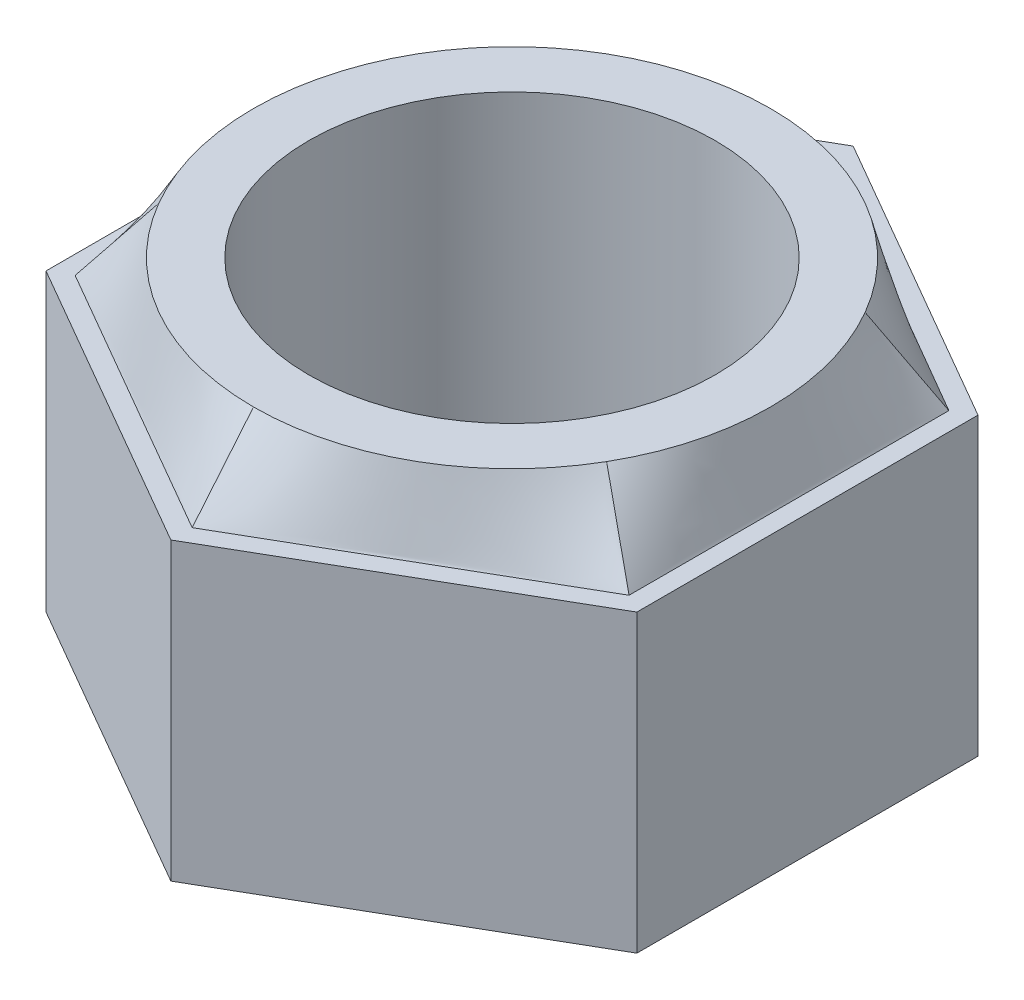
SolidWorks part; units mm, degrees
ref_plane "Front Plane" through (0, 0, 0) normal (0, 0, 1) x (1, 0, 0)
ref_plane "Top Plane" through (0, 0, 0) normal (0, 1, 0) x (1, 0, 0)
ref_plane "Right Plane" through (0, 0, 0) normal (1, 0, 0) x (0, 0, -1)
sketch "Sketch1" plane through (0, 0, 0) normal (0, 1, 0) x (1, 0, 0)
  line L1 (0, 4.6188) -> (-4, 2.3094)
  line L2 (-4, 2.3094) -> (-4, -2.3094)
  line L3 (-4, -2.3094) -> (0, -4.6188)
  line L4 (0, -4.6188) -> (4, -2.3094)
  line L5 (4, -2.3094) -> (4, 2.3094)
  line L6 (4, 2.3094) -> (0, 4.6188)
  circle A0 centre (0, 0) radius 4 construction
  dimension "D1" = 8
extrude "Body" add sketch "Sketch1" along normal blind 4
ref_plane "Plane1" through (0, 5, 0) normal (0, 1, 0) x (1, 0, 0)
sketch "Sketch4" plane through (0, 5, 0) normal (0, 1, 0) x (1, 0, 0)
  circle A2 centre (0, 0) radius 3.5
  dimension "D1" = 7
sketch "Sketch5" plane through (0, 4, 0) normal (0, 1, 0) x (1, 0, 0)
  line L12 (3.75, 2.1651) -> (0, 4.3301)
  line L13 (0, 4.3301) -> (-3.75, 2.1651)
  line L14 (-3.75, 2.1651) -> (-3.75, -2.1651)
  line L15 (-3.75, -2.1651) -> (0, -4.3301)
  line L16 (0, -4.3301) -> (3.75, -2.1651)
  line L17 (3.75, -2.1651) -> (3.75, 2.1651)
  line L18 (3.75, 2.1651) -> (0, 4.3301)
  line L19 (0, 4.3301) -> (-3.75, 2.1651)
  line L20 (-3.75, 2.1651) -> (-3.75, -2.1651)
  line L21 (-3.75, -2.1651) -> (0, -4.3301)
  line L22 (0, -4.3301) -> (3.75, -2.1651)
  line L23 (3.75, -2.1651) -> (3.75, 2.1651)
  dimension "D1" = 0.25
loft "Loft1" add profiles "Sketch5", "Sketch4"
hole_wizard "M5 Clearance Hole2" positions "Sketch6" profile "Sketch7" hole size "M5" standard "ANSI Metric" end condition through all
sketch "Sketch6" plane through (0, 5, 0) normal (0, 1, 0) x (1, 0, 0)
  point P0 (0, 0)
sketch "Sketch7" plane through (0, 5, 0) normal (1, 0, 0) x (0, 0, 1)
  line L0 (0, 0) -> (0, 5)
  line L1 (0, 5) -> (2.75, 5)
  line L2 (2.75, 5) -> (2.75, 0)
  line L5 (2.75, 0) -> (0, 0)
  line L11 (0, -6.35) -> (0, 107.95) construction
  dimension "Thru Hole Dia." = 5.5
  dimension "Thru Hole Depth" = 5
